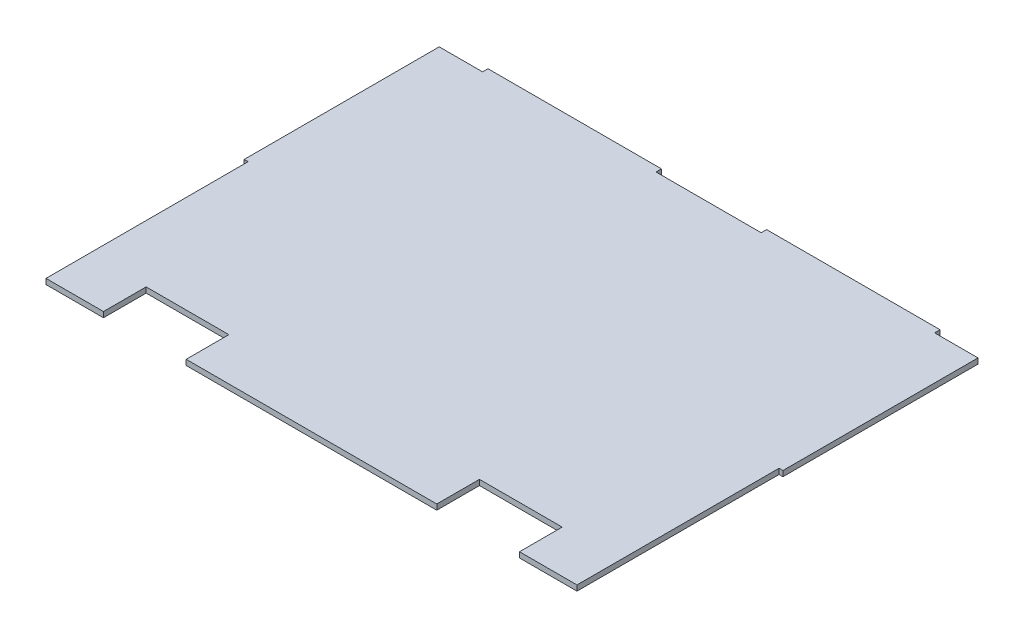
SolidWorks part; units mm, degrees
material "Custom Plastic"
ref_plane "X-Y Datum" through (0, 0, 0) normal (0, 0, 1) x (1, 0, 0)
ref_plane "X-Z Datum" through (0, 0, 0) normal (0, 1, 0) x (1, 0, 0)
ref_plane "Y-Z Datum" through (0, 0, 0) normal (1, 0, 0) x (0, 0, -1)
sketch "Sketch1" plane through (0, 0, 0) normal (0, 0, 1) x (1, 0, 0)
  line L1 (-157.7875, -1.5875) -> (157.7875, -1.5875)
  line L2 (-157.7875, -1.5875) -> (-157.7875, 1.5875)
  line L3 (-157.7875, 1.5875) -> (157.7875, 1.5875)
  line L4 (157.7875, -1.5875) -> (157.7875, 1.5875)
  line L5 (-157.7875, -1.5875) -> (157.7875, 1.5875) construction
  line L6 (-157.7875, 1.5875) -> (157.7875, -1.5875) construction
  point P0 (0, 0)
  dimension "D1" = 315.575
  dimension "D2" = 3.175
extrude "Boss-Extrude1" add sketch "Sketch1" along normal blind 235.775
sketch "Sketch3" plane through (0, 0, 0) normal (0, 0, -1) x (-1, 0, 0)
  line L0 (-157.7875, 0) -> (-81.5875, 0) construction
  line L1 (-157.7875, -1.5875) -> (-157.7875, 1.5875) construction
  line L2 (-157.7875, 1.5875) -> (157.7875, 1.5875) construction
  line L3 (-132.3875, -1.5875) -> (-30.7875, -1.5875)
  line L4 (-132.3875, -1.5875) -> (-132.3875, 1.5875)
  line L5 (-132.3875, 1.5875) -> (-30.7875, 1.5875)
  line L6 (-30.7875, -1.5875) -> (-30.7875, 1.5875)
  line L7 (-132.3875, -1.5875) -> (-30.7875, 1.5875) construction
  line L8 (-132.3875, 1.5875) -> (-30.7875, -1.5875) construction
  line L14 (-157.7875, 1.5875) -> (-132.3875, 1.5875)
  line L15 (-157.7875, 1.5875) -> (-157.7875, -1.5875)
  line L16 (-157.7875, -1.5875) -> (-132.3875, -1.5875)
  line L17 (-132.3875, 1.5875) -> (-132.3875, -1.5875)
  line L19 (-30.7875, 1.5875) -> (-30.7875, -1.5875)
  line L20 (0, 43.0151) -> (0, -43.0151) construction
  line L21 (30.7875, -1.5875) -> (30.7875, 1.5875)
  line L22 (132.3875, -1.5875) -> (132.3875, 1.5875)
  line L23 (132.3875, 1.5875) -> (30.7875, 1.5875)
  line L24 (132.3875, -1.5875) -> (30.7875, 1.5875) construction
  line L25 (132.3875, -1.5875) -> (30.7875, -1.5875)
  line L26 (132.3875, 1.5875) -> (30.7875, -1.5875) construction
  dimension "D1" = 76.2
  dimension "D2" = 101.6
extrude "Cut-Extrude1" cut sketch "Sketch3" against normal blind 3.175
sketch "Sketch5" plane through (0, 1.5875, 0) normal (0, 1, 0) x (1, 0, 0)
  line L1 (-157.7875, -235.775) -> (-155.5015, -235.775)
  line L3 (-157.7875, -235.775) -> (-157.7875, -117.411)
  line L5 (-157.7875, -117.411) -> (-155.5015, -117.411)
  line L6 (-155.5015, -235.775) -> (-155.5015, -117.411)
  dimension "D1" = 118.364
  dimension "D2" = 2.286
extrude "Cut-Extrude2" cut sketch "Sketch5" against normal blind 3.175 and the other way through all
mirror "Mirror1" about plane through (0, 0, 0) normal (1, 0, 0) of "Cut-Extrude2"
sketch "Sketch6" plane through (0, 1.5875, 0) normal (0, 1, 0) x (1, 0, 0)
  line L5 (155.5015, -235.775) -> (-155.5015, -235.775) construction
  line L6 (-121.8431, -210.775) -> (-73.389, -210.775)
  line L7 (-121.8431, -210.775) -> (-121.8431, -235.775)
  line L8 (-121.8431, -235.775) -> (-73.389, -235.775)
  line L9 (-73.389, -210.775) -> (-73.389, -235.775)
extrude "Cut-Extrude4" cut sketch "Sketch6" against normal through all
mirror "Mirror2" about plane through (0, 0, 0) normal (1, 0, 0) of "Cut-Extrude4"
